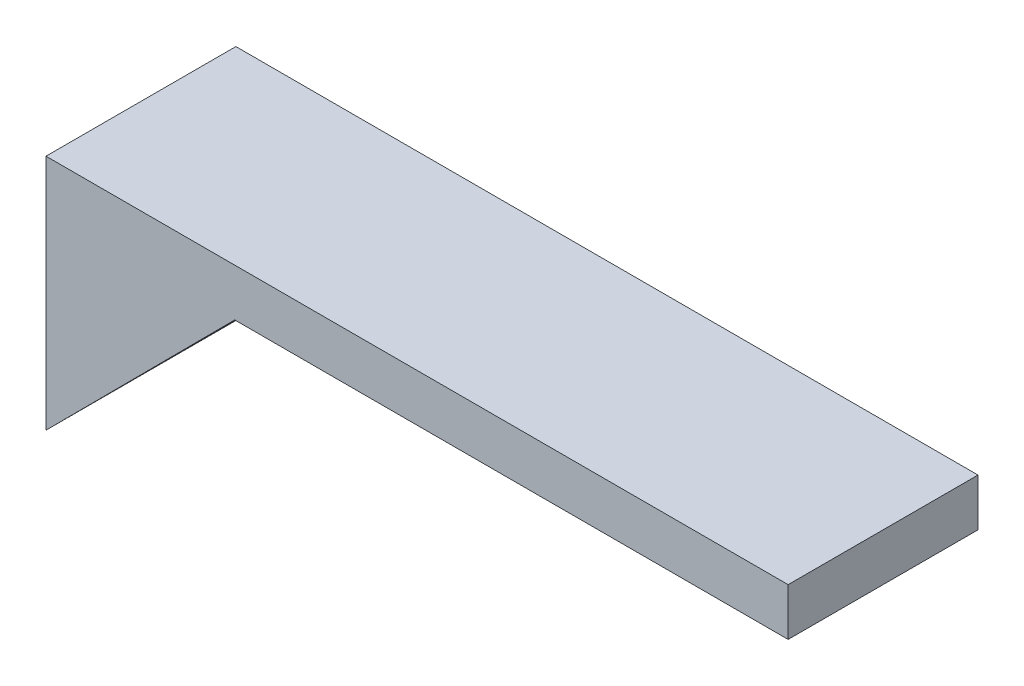
SolidWorks part; units mm, degrees
ref_plane "Front Plane" through (0, 0, 0) normal (0, 0, 1) x (1, 0, 0)
ref_plane "Top Plane" through (0, 0, 0) normal (0, 1, 0) x (1, 0, 0)
ref_plane "Right Plane" through (0, 0, 0) normal (1, 0, 0) x (0, 0, -1)
sketch "Sketch1" plane through (0, 0, 0) normal (0, 0, 1) x (1, 0, 0)
  line L0 (0, 0) -> (0, -25.4)
  line L1 (0, -25.4) -> (25.2484, 0)
  line L3 (0, 0) -> (0, 6.35)
  line L4 (0, 6.35) -> (99.2874, 6.35)
  line L5 (99.2874, 6.35) -> (99.2874, 0)
  line L6 (99.2874, 0) -> (25.2484, 0)
  dimension "D1" = 35.814
  dimension "D2" = 25.4
  dimension "D3" = 6.35
extrude "Boss-Extrude1" add sketch "Sketch1" along normal blind 25.4 contours L6 L1 L0 L3 L4 L5
